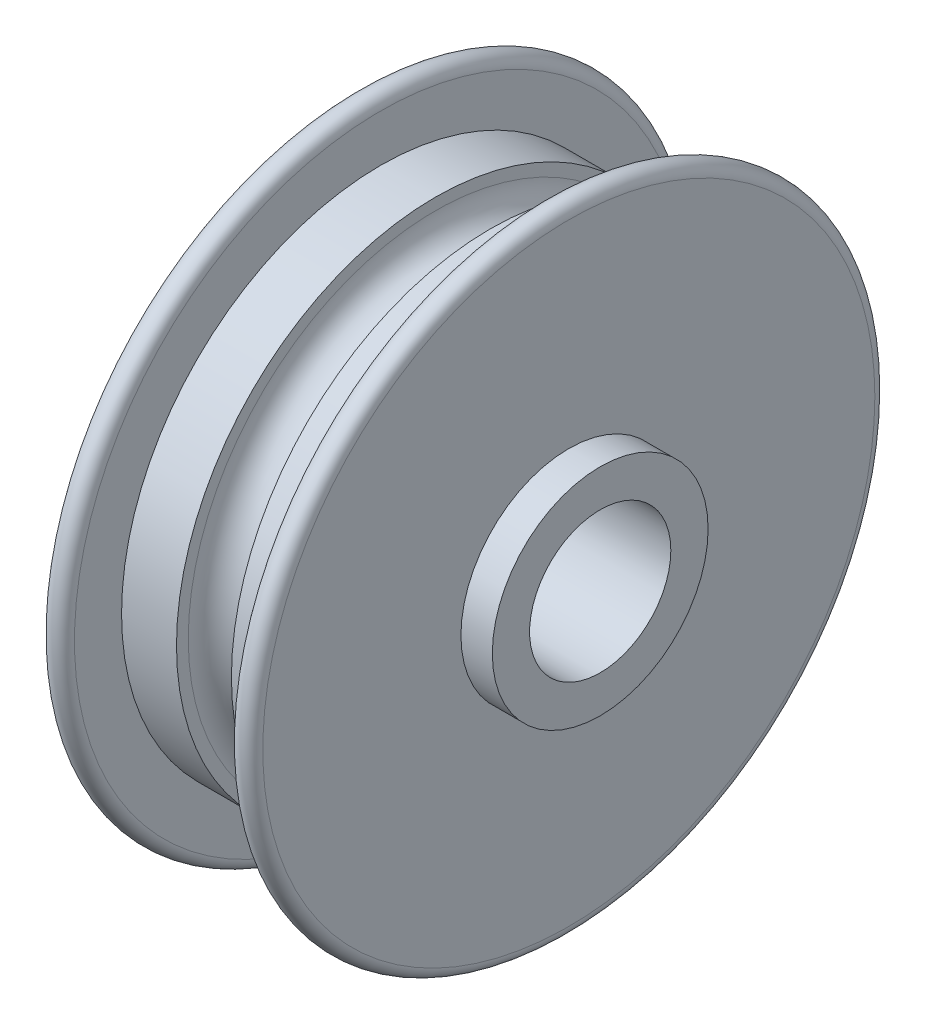
SolidWorks part; units mm, degrees
ref_plane "Front Plane" through (0, 0, 0) normal (0, 0, 1) x (1, 0, 0)
ref_plane "Top Plane" through (0, 0, 0) normal (0, 1, 0) x (1, 0, 0)
ref_plane "Right Plane" through (0, 0, 0) normal (1, 0, 0) x (0, 0, -1)
sketch "Sketch1" plane through (0, 0, 0) normal (0, 0, 1) x (1, 0, 0)
  line L0 (-24.4616, 0) -> (40.6384, 0) construction
  line L1 (26.1759, 13.75) -> (26.1759, 9)
  line L2 (26.1759, 13.75) -> (22.1759, 13.75)
  line L3 (22.1759, 13.75) -> (22.1759, 39)
  line L4 (19.1759, 39) -> (19.1759, 33)
  line L6 (8.6759, 27.25) -> (8.6759, 9)
  line L7 (-8.8241, 9) -> (26.1759, 9)
  line L8 (-8.8241, 13.75) -> (-4.8241, 13.75)
  line L9 (-4.8241, 13.75) -> (-4.8241, 39)
  line L10 (-1.8241, 39) -> (-1.8241, 33)
  line L12 (-8.8241, 13.75) -> (-8.8241, 9)
  line L13 (8.6759, 31.5) -> (14.6934, 31.5) construction
  line L15 (12.1759, 31.5) -> (12.1759, 33)
  line L16 (12.1759, 33) -> (19.1759, 33)
  line L17 (8.6759, 31.5) -> (0.8815, 31.5) construction
  line L18 (-1.8241, 33) -> (5.1759, 33)
  line L19 (5.1759, 33) -> (5.1759, 31.5)
  arc A0 (22.1759, 39) -> (19.1759, 39) centre (20.6759, 39) ccw
  arc A1 (5.1759, 31.5) -> (12.1759, 31.5) centre (8.6759, 31.5) ccw
  arc A2 (-4.8241, 39) -> (-1.8241, 39) centre (-3.3241, 39) cw
  point P20 (20.6759, 40.5)
  dimension "D1" = 1.5
  dimension "D4" = 3.5
  dimension "D2" = 13.5
  dimension "D3" = 17.5
  dimension "D5" = 13.75
  dimension "D6" = 9
  dimension "D7" = 31.5
  dimension "D8" = 40.5
  dimension "D9" = 33
revolve "Revolve1" add sketch "Sketch1" angle 360 about L0
